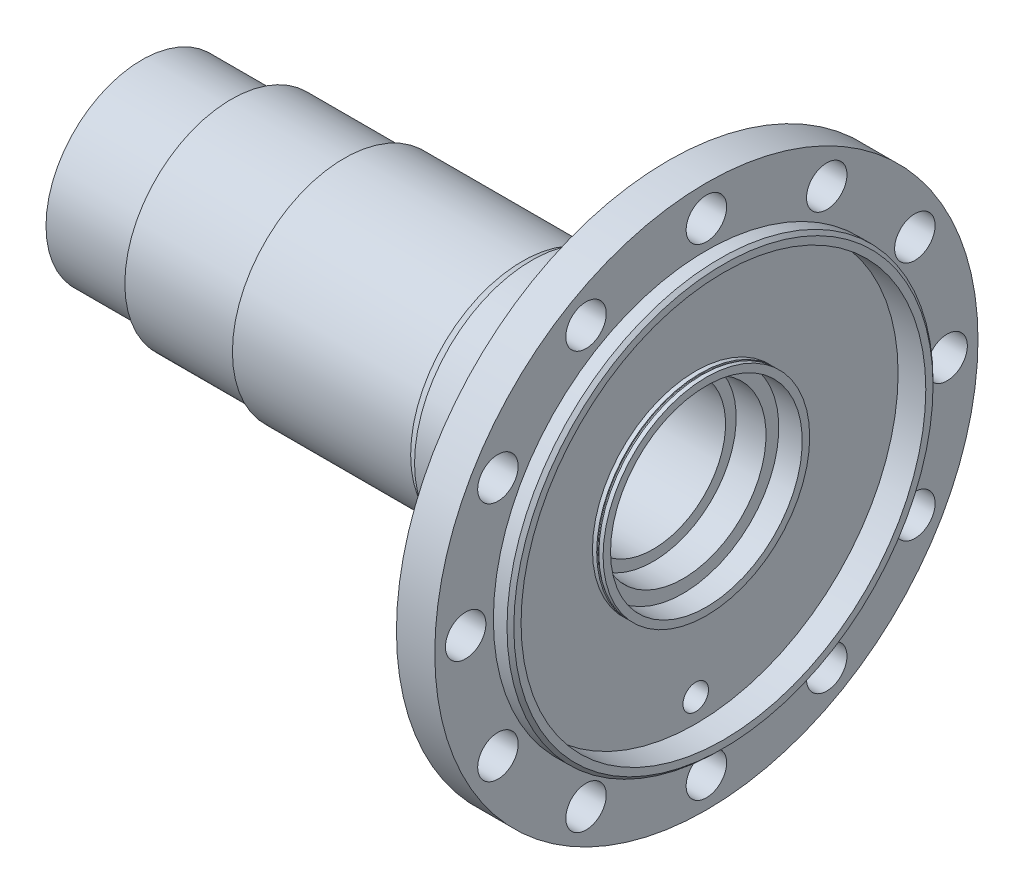
SolidWorks part; units mm, degrees
ref_plane "Спереди" through (0, 0, 0) normal (0, 0, 1) x (1, 0, 0)
ref_plane "Сверху" through (0, 0, 0) normal (0, 1, 0) x (1, 0, 0)
ref_plane "Справа" through (0, 0, 0) normal (1, 0, 0) x (0, 0, -1)
sketch "Эскиз1" plane through (0, 0, 0) normal (0, 0, 1) x (1, 0, 0)
  line L0 (0, 0) -> (273, 0)
  line L1 (0, 0) -> (0, 45)
  line L2 (0, 45) -> (42, 45)
  line L3 (42, 45) -> (42, 50)
  line L4 (42, 50) -> (95, 50)
  line L5 (95, 50) -> (95, 52.5)
  line L6 (95, 52.5) -> (178.6699, 52.5)
  line L7 (178.6699, 52.5) -> (183, 55)
  line L8 (183, 55) -> (213, 55)
  line L9 (215, 57) -> (215, 60.7679)
  line L10 (215, 60.7679) -> (218, 62.5)
  line L11 (218, 62.5) -> (239, 62.5)
  line L12 (239, 62.5) -> (239, 100)
  line L13 (239, 100) -> (247, 100)
  line L14 (247, 100) -> (247, 127.5)
  line L15 (247, 127.5) -> (265, 127.5)
  line L16 (265, 127.5) -> (265, 100)
  line L17 (265, 100) -> (271.4, 100)
  line L18 (271.4, 100) -> (273, 98.4)
  line L19 (273, 98.4) -> (273, 0)
  arc A0 (213, 55) -> (215, 57) centre (213, 57) ccw
revolve "Повернуть1" add sketch "Эскиз1" angle 360 about L0
sketch "Эскиз2" plane through (0, 0, 0) normal (0, 0, 1) x (1, 0, 0)
  line L0 (0, 0) -> (273, 0)
  line L1 (0, 0) -> (0, 31)
  line L2 (0, 31) -> (203.5, 31)
  line L3 (203.5, 31) -> (203.5, 34)
  line L4 (203.5, 34) -> (240, 34)
  line L5 (240, 34) -> (240, 39)
  line L6 (240, 39) -> (254, 39)
  line L7 (254, 39) -> (254, 45)
  line L8 (254, 45) -> (265, 45)
  line L9 (265, 45) -> (265, 95)
  line L10 (265, 95) -> (273, 95)
  line L11 (273, 95) -> (273, 0)
revolve "Вырез-Повернуть1" cut sketch "Эскиз2" angle 360 about L0
sketch "Эскиз3" plane through (0, 0, 0) normal (0, 0, 1) x (1, 0, 0)
  line L0 (0, 0) -> (273, 0) construction
  line L1 (260, 48.5) -> (262, 48.5)
  line L2 (262, 48.5) -> (262, 95)
  line L3 (262, 95) -> (260, 95)
  line L4 (260, 95) -> (260, 48.5)
revolve "Rear_recess_left" cut sketch "Эскиз3" angle 360 about L0
sketch "Эскиз4" plane through (0, 0, 0) normal (0, 0, 1) x (1, 0, 0)
  line L0 (0, 0) -> (273, 0) construction
  line L1 (263, 48) -> (263, 95)
  line L2 (263, 95) -> (262, 95)
  line L3 (262, 95) -> (262, 48)
  arc A0 (262, 48) -> (262.5, 47.5) centre (262.5, 48) ccw
  arc A1 (262.5, 47.5) -> (263, 48) centre (262.5, 48) ccw
revolve "Collar_groove_nominal" cut sketch "Эскиз4" angle 360 about L0
sketch "Эскиз5" plane through (0, 0, 0) normal (0, 0, 1) x (1, 0, 0)
  line L0 (0, 0) -> (273, 0) construction
  line L1 (263, 48.5) -> (265, 48.5)
  line L2 (265, 48.5) -> (265, 95)
  line L3 (265, 95) -> (263, 95)
  line L4 (263, 95) -> (263, 48.5)
revolve "Rear_recess_lip" cut sketch "Эскиз5" angle 360 about L0
sketch "Эскиз6" plane through (0, 0, 0) normal (1, 0, 0) x (0, 0, -1)
  circle A0 centre (0, 113) radius 9.5
extrude "Вырез-Вытянуть1" cut sketch "Эскиз6" along normal through all
sketch "Эскиз7" plane through (0, 0, 0) normal (1, 0, 0) x (0, 0, -1)
  circle A0 centre (-56.5, 97.8609) radius 9.5
extrude "Вырез-Вытянуть2" cut sketch "Эскиз7" along normal through all
sketch "Эскиз8" plane through (0, 0, 0) normal (1, 0, 0) x (0, 0, -1)
  circle A0 centre (-97.8609, 56.5) radius 9.5
extrude "Вырез-Вытянуть3" cut sketch "Эскиз8" along normal through all
sketch "Эскиз9" plane through (0, 0, 0) normal (1, 0, 0) x (0, 0, -1)
  circle A0 centre (-113, 0) radius 9.5
extrude "Вырез-Вытянуть4" cut sketch "Эскиз9" along normal through all
sketch "Эскиз10" plane through (0, 0, 0) normal (1, 0, 0) x (0, 0, -1)
  circle A0 centre (-97.8609, -56.5) radius 9.5
extrude "Вырез-Вытянуть5" cut sketch "Эскиз10" along normal through all
sketch "Эскиз11" plane through (0, 0, 0) normal (1, 0, 0) x (0, 0, -1)
  circle A0 centre (-56.5, -97.8609) radius 9.5
extrude "Вырез-Вытянуть6" cut sketch "Эскиз11" along normal through all
sketch "Эскиз12" plane through (0, 0, 0) normal (1, 0, 0) x (0, 0, -1)
  circle A0 centre (0, -113) radius 9.5
extrude "Вырез-Вытянуть7" cut sketch "Эскиз12" along normal through all
sketch "Эскиз13" plane through (0, 0, 0) normal (1, 0, 0) x (0, 0, -1)
  circle A0 centre (56.5, -97.8609) radius 9.5
extrude "Вырез-Вытянуть8" cut sketch "Эскиз13" along normal through all
sketch "Эскиз14" plane through (0, 0, 0) normal (1, 0, 0) x (0, 0, -1)
  circle A0 centre (97.8609, -56.5) radius 9.5
extrude "Вырез-Вытянуть9" cut sketch "Эскиз14" along normal through all
sketch "Эскиз15" plane through (0, 0, 0) normal (1, 0, 0) x (0, 0, -1)
  circle A0 centre (113, 0) radius 9.5
extrude "Вырез-Вытянуть10" cut sketch "Эскиз15" along normal through all
sketch "Эскиз16" plane through (0, 0, 0) normal (1, 0, 0) x (0, 0, -1)
  circle A0 centre (97.8609, 56.5) radius 9.5
extrude "Вырез-Вытянуть11" cut sketch "Эскиз16" along normal through all
sketch "Эскиз17" plane through (0, 0, 0) normal (1, 0, 0) x (0, 0, -1)
  circle A0 centre (56.5, 97.8609) radius 9.5
extrude "Вырез-Вытянуть12" cut sketch "Эскиз17" along normal through all
sketch "Эскиз18" plane through (0, 0, 0) normal (1, 0, 0) x (0, 0, -1)
  circle A0 centre (0, -84) radius 6
extrude "Вырез-Вытянуть13" cut sketch "Эскиз18" along normal through all
